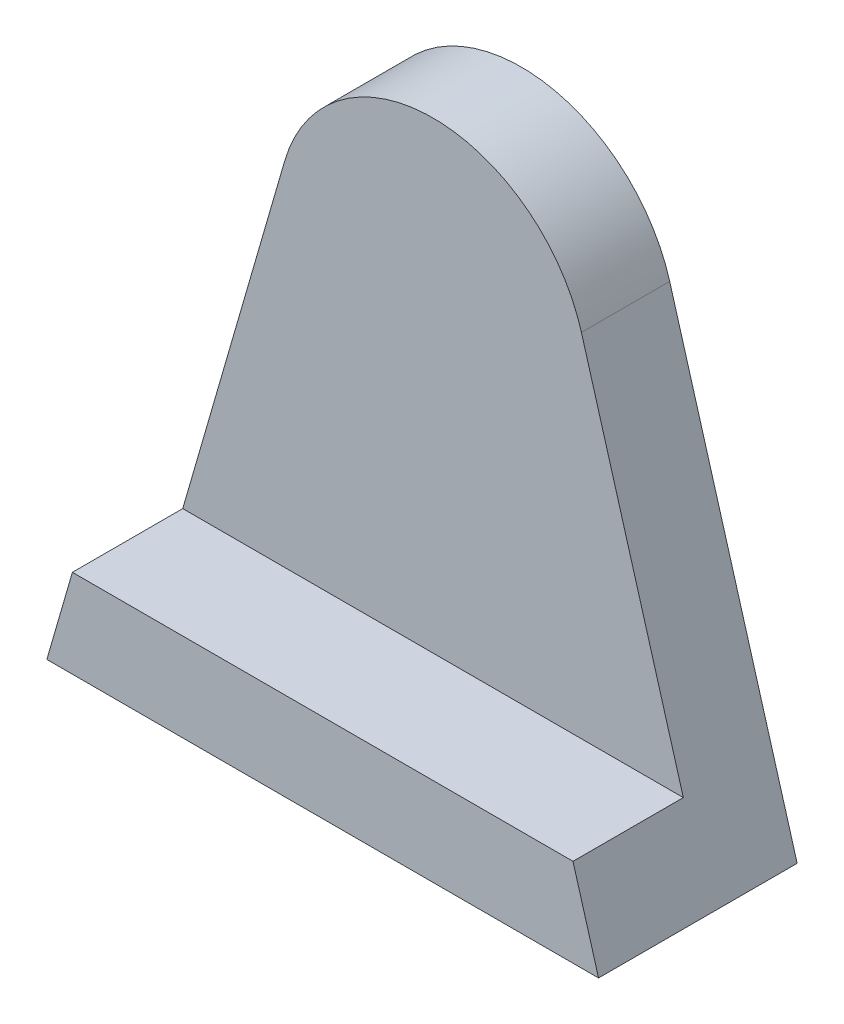
SolidWorks part; units mm, degrees
ref_plane "Front" through (0, 0, 0) normal (0, 0, 1) x (1, 0, 0)
ref_plane "Top" through (0, 0, 0) normal (0, 1, 0) x (1, 0, 0)
ref_plane "Right" through (0, 0, 0) normal (1, 0, 0) x (0, 0, -1)
sketch "Sketch1" plane through (0, 0, 0) normal (0, 0, 1) x (1, 0, 0)
  line L0 (-12.5, 0) -> (-6.7238, 19.9471)
  line L1 (6.7238, 19.9471) -> (12.5, 0)
  line L2 (12.5, 0) -> (-12.5, 0)
  arc A1 (-6.7238, 19.9471) -> (6.7238, 19.9471) centre (0, 18) cw
  point P7 (0, 0)
  point P9 (0, 25)
  dimension "D3" = 7
  dimension "D1" = 25
  dimension "D2" = 25
extrude "Boss-Extrude1" add sketch "Sketch1" along normal blind 4
sketch "Sketch2" plane through (0, 0, 4) normal (0, 0, 1) x (1, 0, 0)
  line L0 (-12.5, 0) -> (12.5, 0)
  line L1 (12.5, 0) -> (11.3417, 4)
  line L2 (12.5, 0) -> (6.7238, 19.9471) construction
  line L3 (11.3417, 4) -> (-11.3417, 4)
  line L4 (-6.7238, 19.9471) -> (-12.5, 0) construction
  line L5 (-11.3417, 4) -> (-12.5, 0)
  dimension "D1" = 4
extrude "Boss-Extrude2" add sketch "Sketch2" along normal blind 5
